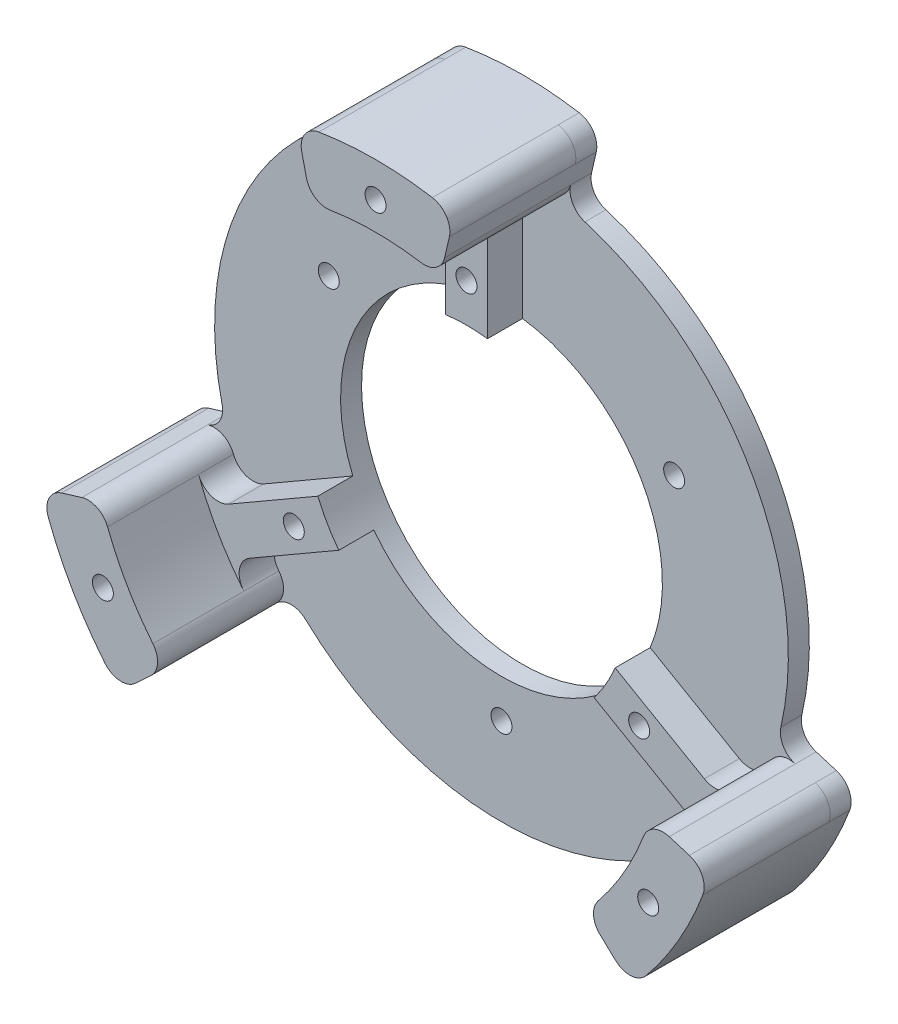
SolidWorks part; units mm, degrees
material "7050-T73510"
ref_plane "前视基准面" through (0, 0, 0) normal (0, 0, 1) x (1, 0, 0)
ref_plane "上视基准面" through (0, 0, 0) normal (0, 1, 0) x (1, 0, 0)
ref_plane "右视基准面" through (0, 0, 0) normal (1, 0, 0) x (0, 0, -1)
sketch "草图1" plane through (0, 0, 0) normal (0, 0, 1) x (1, 0, 0)
  circle A0 centre (0, 0) radius 50
  circle A1 centre (0, 0) radius 23
  dimension "D1" = 100
  dimension "D2" = 46
extrude "凸台-拉伸1" add sketch "草图1" along normal blind 3
sketch "草图3" plane through (0, 0, 3) normal (0, 0, 1) x (1, 0, 0)
  line L0 (-63.4676, 0) -> (72.1344, 0) construction
  line L1 (0, 53.8008) -> (0, -53.9341) construction
  line L2 (-9.8748, 42.7725) -> (-10.5511, 45.702)
  line L3 (9.8748, 42.7725) -> (10.5511, 45.702)
  line L4 (-9.223, 39.9492) -> (0, 0) construction
  line L5 (0, 0) -> (9.223, 39.9492) construction
  line L6 (41.9795, -12.8344) -> (44.8547, -13.7134)
  line L7 (32.1047, -29.9381) -> (34.3035, -31.9886)
  line L8 (-32.1047, -29.9381) -> (-34.3035, -31.9886)
  line L9 (-41.9795, -12.8344) -> (-44.8547, -13.7134)
  arc A1 (-8.1149, 49.3371) -> (8.1149, 49.3371) centre (0, 0) cw
  arc A2 (-6.4777, 40.485) -> (6.4777, 40.485) centre (0, 0) cw
  arc A3 (-10.5511, 45.702) -> (-8.1149, 49.3371) centre (-7.628, 46.3769) cw
  arc A4 (10.5511, 45.702) -> (8.1149, 49.3371) centre (7.628, 46.3769) ccw
  arc A5 (9.8748, 42.7725) -> (6.4777, 40.485) centre (6.9517, 43.4474) cw
  arc A6 (-6.4777, 40.485) -> (-9.8748, 42.7725) centre (-6.9517, 43.4474) cw
  circle A7 centre (0, 0) radius 50 construction
  arc A8 (38.2999, -14.6327) -> (31.8222, -25.8524) centre (0, 0) cw
  arc A9 (38.2999, -14.6327) -> (41.9795, -12.8344) centre (41.1024, -15.7033) cw
  arc A10 (44.8547, -13.7134) -> (46.7846, -17.6408) centre (43.9776, -16.5824) cw
  arc A11 (46.7846, -17.6408) -> (38.6697, -31.6963) centre (0, 0) cw
  arc A12 (34.3035, -31.9886) -> (38.6697, -31.6963) centre (36.3495, -29.7945) ccw
  arc A13 (32.1047, -29.9381) -> (31.8222, -25.8524) centre (34.1507, -27.744) cw
  arc A14 (-31.8222, -25.8524) -> (-38.2999, -14.6327) centre (0, 0) cw
  arc A15 (-31.8222, -25.8524) -> (-32.1047, -29.9381) centre (-34.1507, -27.744) cw
  arc A16 (-34.3035, -31.9886) -> (-38.6697, -31.6963) centre (-36.3495, -29.7945) cw
  arc A17 (-38.6697, -31.6963) -> (-46.7846, -17.6408) centre (0, 0) cw
  arc A18 (-44.8547, -13.7134) -> (-46.7846, -17.6408) centre (-43.9776, -16.5824) ccw
  arc A19 (-41.9795, -12.8344) -> (-38.2999, -14.6327) centre (-41.1024, -15.7033) cw
  point P49 (0, 0)
  dimension "D2" = 41
  dimension "D3" = 3
  dimension "D1" = 13
  dimension "D4" = 26
  dimension "D5" = 3
extrude "凸台-拉伸2" add sketch "草图3" along normal blind 18
sketch "草图9" plane through (0, 0, 3) normal (0, 0, 1) x (1, 0, 0)
  line L0 (0, 0) -> (-36.5677, -34.0999) construction
  line L1 (-34.3035, -31.9886) -> (-32.1047, -29.9381) construction
  line L2 (0, 5.8456) -> (0, -56.9768) construction
  line L3 (0, 0) -> (36.5677, -34.0999) construction
  line L4 (-29.9855, -27.9619) -> (-36.5677, -34.0999)
  line L5 (29.9855, -27.9619) -> (36.5677, -34.0999)
  line L6 (-9.223, 39.9492) -> (-11.2476, 48.7185)
  line L7 (-39.2085, -11.9872) -> (-47.8152, -14.6186)
  line L8 (39.2085, -11.9872) -> (47.8152, -14.6186)
  line L9 (9.223, 39.9492) -> (11.2476, 48.7185)
  arc A0 (-38.6697, -31.6963) -> (38.6697, -31.6963) centre (0, 0) ccw construction
  arc A1 (-29.9855, -27.9619) -> (29.9855, -27.9619) centre (0, 0) ccw
  arc A2 (36.5677, -34.0999) -> (-36.5677, -34.0999) centre (0, 0) cw
  arc A3 (-9.223, 39.9492) -> (-39.2085, -11.9872) centre (0, 0) ccw
  arc A4 (-47.8152, -14.6186) -> (-11.2476, 48.7185) centre (0, 0) cw
  arc A5 (39.2085, -11.9872) -> (9.223, 39.9492) centre (0, 0) ccw
  arc A6 (11.2476, 48.7185) -> (47.8152, -14.6186) centre (0, 0) cw
  point P27 (0, 0)
  dimension "D1" = 41
  dimension "D2" = 3
extrude "切除-拉伸3" cut sketch "草图9" against normal blind 10
fillet "圆角1" radius 3 12 edges at (47.8152, -14.6186, 1.5) (39.2085, -11.9872, 1.5) (9.223, 39.9492, 1.5) (11.2476, 48.7185, 1.5) (-11.2476, 48.7185, 1.5) (-9.223, 39.9492, 1.5) (-39.2085, -11.9872, 1.5) (-47.8152, -14.6186, 1.5) (-36.5677, -34.0999, 1.5) (-29.9855, -27.9619, 1.5) (29.9855, -27.9619, 1.5) (36.5677, -34.0999, 1.5)
sketch "草图10" plane through (0, 0, 3) normal (0, 0, 1) x (1, 0, 0)
  line L0 (0, 53.2703) -> (0, -14.996) construction
  line L1 (-3, 22.8035) -> (-3, 40.8901)
  line L2 (3, 22.8035) -> (3, 40.8901)
  line L3 (21.2484, -8.8037) -> (36.9119, -17.847)
  line L4 (18.2484, -13.9998) -> (33.9119, -23.0431)
  line L5 (-18.2484, -13.9998) -> (-33.9119, -23.0431)
  line L6 (-21.2484, -8.8037) -> (-36.9119, -17.847)
  circle A0 centre (0, 0) radius 23 construction
  arc A1 (6.4777, 40.485) -> (-6.4777, 40.485) centre (0, 0) ccw construction
  arc A2 (6.4777, 40.485) -> (-6.4777, 40.485) centre (0, 0) ccw construction
  arc A3 (3, 22.8035) -> (-3, 22.8035) centre (0, 0) ccw
  arc A4 (3, 40.8901) -> (-3, 40.8901) centre (0, 0) ccw
  arc A5 (33.9119, -23.0431) -> (36.9119, -17.847) centre (0, 0) ccw
  arc A6 (18.2484, -13.9998) -> (21.2484, -8.8037) centre (0, 0) ccw
  arc A7 (-36.9119, -17.847) -> (-33.9119, -23.0431) centre (0, 0) ccw
  arc A8 (-21.2484, -8.8037) -> (-18.2484, -13.9998) centre (0, 0) ccw
  point P25 (0, 0)
  dimension "D1" = 6
  dimension "D2" = 3
extrude "凸台-拉伸3" add sketch "草图10" along normal blind 5
fillet "圆角2" radius 3 6 edges at (33.9119, -23.0431, 5.5) (36.9119, -17.847, 5.5) (-36.9119, -17.847, 5.5) (-33.9119, -23.0431, 5.5) (-3, 40.8901, 5.5) (3, 40.8901, 5.5)
sketch "草图12" plane through (0, 0, 0) normal (0, 0, -1) x (-1, 0, 0)
  circle A0 centre (0, 0) radius 28.5 construction
  circle A1 centre (0, 0) radius 45 construction
  circle A2 centre (0, 45) radius 1.5
  circle A3 centre (0, 28.5) radius 1.5
  circle A4 centre (38.9711, -22.5) radius 1.5
  circle A5 centre (-38.9711, -22.5) radius 1.5
  circle A6 centre (24.6817, 14.25) radius 1.5
  circle A7 centre (24.6817, -14.25) radius 1.5
  circle A8 centre (0, -28.5) radius 1.5
  circle A9 centre (-24.6817, -14.25) radius 1.5
  circle A10 centre (-24.6817, 14.25) radius 1.5
  point P14 (0, 0)
  point P26 (0, 0)
  dimension "D1" = 90
  dimension "D2" = 57
  dimension "D3" = 3
  dimension "D4" = 3
  dimension "D5" = 3
  dimension "D6" = 6
extrude "切除-拉伸5" cut sketch "草图12" against normal through all
